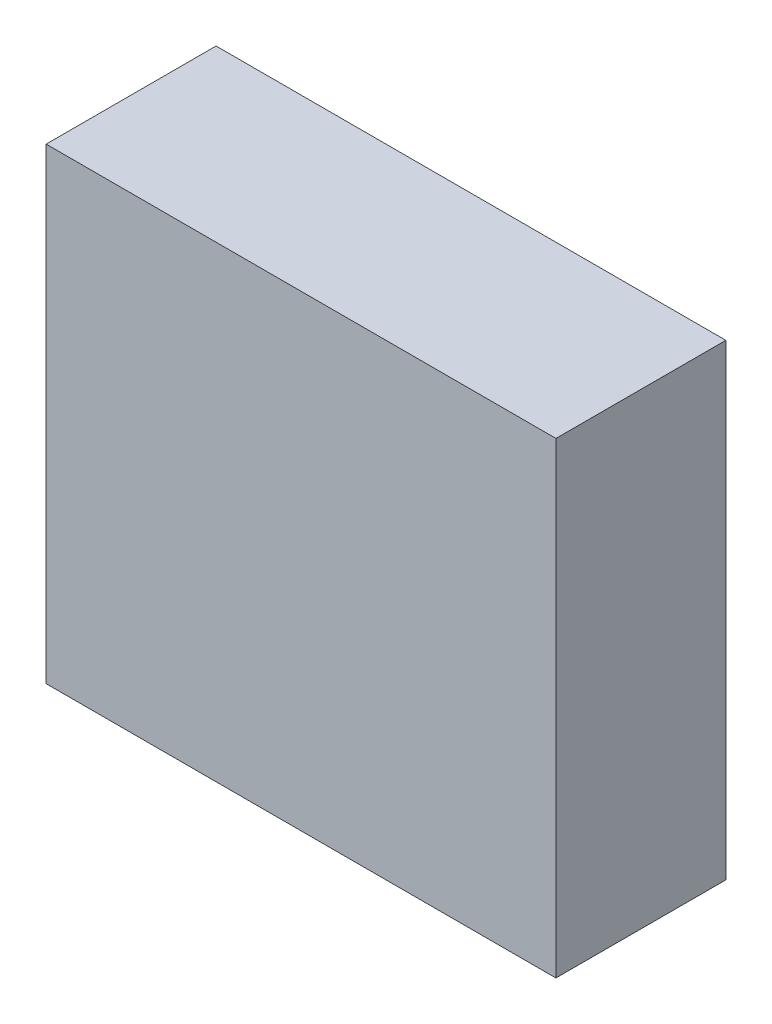
SolidWorks part; units mm, degrees
material "Low Carbon Steel"
ref_plane "Front Plane" through (0, 0, 0) normal (0, 0, 1) x (1, 0, 0)
ref_plane "Top Plane" through (0, 0, 0) normal (0, 1, 0) x (1, 0, 0)
ref_plane "Right Plane" through (0, 0, 0) normal (1, 0, 0) x (0, 0, -1)
sketch "Sketch1" plane through (0, 0, 0) normal (0, 0, 1) x (1, 0, 0)
  line L0 (76.2, 69.85) -> (-76.2, -69.85) construction
  line L1 (-76.2, 69.85) -> (76.2, 69.85)
  line L2 (-76.2, 69.85) -> (-76.2, -69.85)
  line L3 (-76.2, -69.85) -> (76.2, -69.85)
  line L4 (76.2, 69.85) -> (76.2, -69.85)
  dimension "D1" = 139.7
  dimension "D2" = 152.4
extrude "Boss-Extrude1" add sketch "Sketch1" along normal blind 50.8
other "Freeze***"
